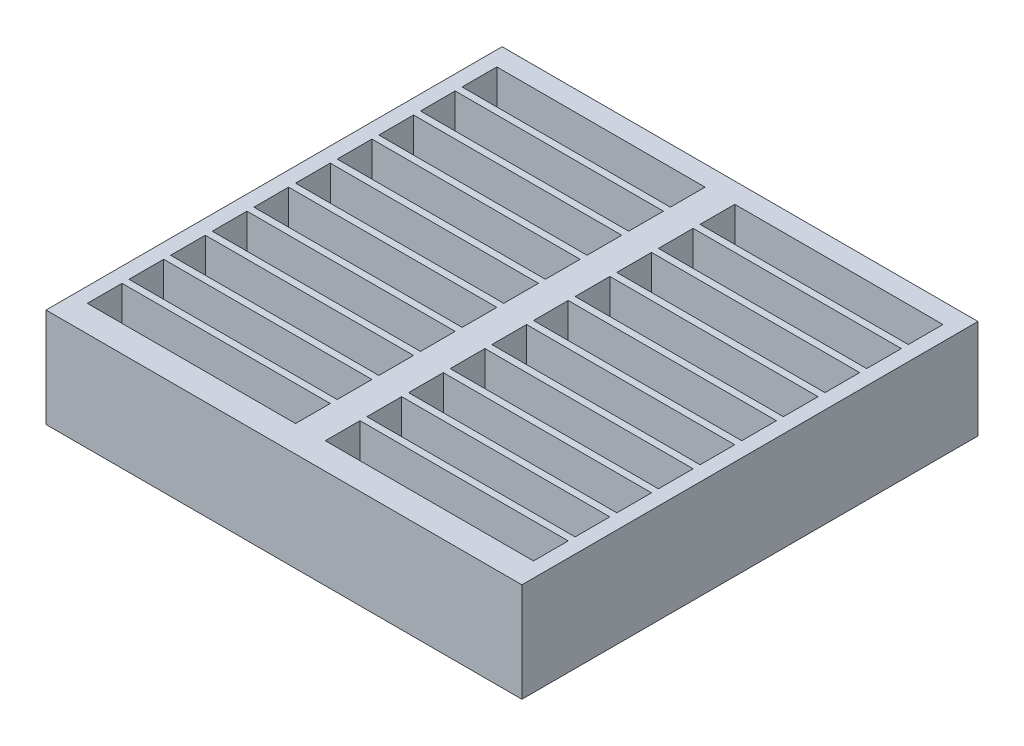
SolidWorks part; units mm, degrees
material "Plastique personnalisé"
ref_plane "Plan de face" through (0, 0, 0) normal (0, 0, 1) x (1, 0, 0)
ref_plane "Plan de dessus" through (0, 0, 0) normal (0, 1, 0) x (1, 0, 0)
ref_plane "Plan de droite" through (0, 0, 0) normal (1, 0, 0) x (0, 0, -1)
sketch "Esquisse1" plane through (0, 0, 0) normal (0, 1, 0) x (1, 0, 0)
  line L1 (0, 0) -> (48, 0)
  line L2 (0, 0) -> (0, 46)
  line L3 (0, 46) -> (48, 46)
  line L4 (48, 0) -> (48, 46)
  dimension "D1" = 48
  dimension "D2" = 46
extrude "Boss.-Extru.1" add sketch "Esquisse1" along normal blind 10
sketch "Esquisse2" plane through (0, 10, 0) normal (0, 1, 0) x (1, 0, 0)
  line L0 (48, 0) -> (0, 0) construction
  line L1 (0, 0) -> (24, 0) construction
  line L2 (24, 0) -> (24, 46) construction
  line L3 (48, 46) -> (0, 46) construction
  line L4 (48, 23) -> (0, 23) construction
  line L5 (48, 0) -> (48, 46) construction
  line L6 (0, 46) -> (0, 0) construction
  line L7 (48, 0) -> (48, 23) construction
  line L8 (48, 11.5) -> (0, 11.5) construction
  line L9 (48, 46) -> (24, 46) construction
  line L10 (36, 46) -> (36, 0) construction
sketch "Esquisse3" plane through (0, 10, 0) normal (0, 1, 0) x (1, 0, 0)
  line L0 (25.5, 2.6693) -> (46.5, 2.6693)
  line L1 (36, 46) -> (36, 0) construction
  line L2 (46.5, 2.6693) -> (46.5, 6.1693)
  line L3 (46.5, 6.1693) -> (25.5, 6.1693)
  line L4 (36, 2.6693) -> (36, 6.1693) construction
  line L5 (25.5, 2.6693) -> (25.5, 6.1693)
  line L6 (25.5, 6.8693) -> (46.5, 6.8693)
  line L7 (46.5, 6.8693) -> (46.5, 10.3693)
  line L8 (46.5, 10.3693) -> (25.5, 10.3693)
  line L9 (25.5, 6.8693) -> (25.5, 10.3693)
  line L10 (25.5, 11.0693) -> (46.5, 11.0693)
  line L11 (46.5, 11.0693) -> (46.5, 14.5693)
  line L12 (46.5, 14.5693) -> (25.5, 14.5693)
  line L13 (25.5, 11.0693) -> (25.5, 14.5693)
  line L14 (25.5, 15.2693) -> (46.5, 15.2693)
  line L15 (46.5, 15.2693) -> (46.5, 18.7693)
  line L16 (46.5, 18.7693) -> (25.5, 18.7693)
  line L17 (25.5, 15.2693) -> (25.5, 18.7693)
  line L18 (25.5, 19.4693) -> (46.5, 19.4693)
  line L19 (46.5, 19.4693) -> (46.5, 22.9693)
  line L20 (46.5, 22.9693) -> (25.5, 22.9693)
  line L21 (25.5, 19.4693) -> (25.5, 22.9693)
  line L22 (25.5, 23.6693) -> (46.5, 23.6693)
  line L23 (46.5, 23.6693) -> (46.5, 27.1693)
  line L24 (46.5, 27.1693) -> (25.5, 27.1693)
  line L25 (25.5, 23.6693) -> (25.5, 27.1693)
  line L26 (25.5, 27.8693) -> (46.5, 27.8693)
  line L27 (46.5, 27.8693) -> (46.5, 31.3693)
  line L28 (46.5, 31.3693) -> (25.5, 31.3693)
  line L29 (25.5, 27.8693) -> (25.5, 31.3693)
  line L30 (25.5, 32.0693) -> (46.5, 32.0693)
  line L31 (46.5, 32.0693) -> (46.5, 35.5693)
  line L32 (46.5, 35.5693) -> (25.5, 35.5693)
  line L33 (25.5, 32.0693) -> (25.5, 35.5693)
  line L34 (25.5, 36.2693) -> (46.5, 36.2693)
  line L35 (46.5, 36.2693) -> (46.5, 39.7693)
  line L36 (46.5, 39.7693) -> (25.5, 39.7693)
  line L37 (25.5, 36.2693) -> (25.5, 39.7693)
  line L38 (25.5, 40.4693) -> (46.5, 40.4693)
  line L39 (46.5, 40.4693) -> (46.5, 43.9693)
  line L40 (46.5, 43.9693) -> (25.5, 43.9693)
  line L41 (25.5, 40.4693) -> (25.5, 43.9693)
  line L43 (24, 0) -> (24, 46) construction
  line L44 (48, 0) -> (0, 0) construction
  line L45 (22.5, 2.6693) -> (22.5, 6.1693)
  line L46 (1.5, 6.1693) -> (22.5, 6.1693)
  line L47 (1.5, 2.6693) -> (1.5, 6.1693)
  line L48 (22.5, 2.6693) -> (1.5, 2.6693)
  line L49 (22.5, 6.8693) -> (22.5, 10.3693)
  line L50 (1.5, 10.3693) -> (22.5, 10.3693)
  line L51 (1.5, 6.8693) -> (1.5, 10.3693)
  line L52 (22.5, 6.8693) -> (1.5, 6.8693)
  line L53 (22.5, 11.0693) -> (22.5, 14.5693)
  line L54 (1.5, 14.5693) -> (22.5, 14.5693)
  line L55 (1.5, 11.0693) -> (1.5, 14.5693)
  line L56 (22.5, 11.0693) -> (1.5, 11.0693)
  line L57 (22.5, 15.2693) -> (22.5, 18.7693)
  line L58 (1.5, 18.7693) -> (22.5, 18.7693)
  line L59 (1.5, 15.2693) -> (1.5, 18.7693)
  line L60 (22.5, 15.2693) -> (1.5, 15.2693)
  line L61 (22.5, 19.4693) -> (22.5, 22.9693)
  line L62 (1.5, 22.9693) -> (22.5, 22.9693)
  line L63 (1.5, 19.4693) -> (1.5, 22.9693)
  line L64 (22.5, 19.4693) -> (1.5, 19.4693)
  line L65 (22.5, 23.6693) -> (22.5, 27.1693)
  line L66 (1.5, 27.1693) -> (22.5, 27.1693)
  line L67 (1.5, 23.6693) -> (1.5, 27.1693)
  line L68 (22.5, 23.6693) -> (1.5, 23.6693)
  line L69 (22.5, 27.8693) -> (22.5, 31.3693)
  line L70 (1.5, 31.3693) -> (22.5, 31.3693)
  line L71 (1.5, 27.8693) -> (1.5, 31.3693)
  line L72 (22.5, 27.8693) -> (1.5, 27.8693)
  line L73 (22.5, 32.0693) -> (22.5, 35.5693)
  line L74 (1.5, 35.5693) -> (22.5, 35.5693)
  line L75 (1.5, 32.0693) -> (1.5, 35.5693)
  line L76 (22.5, 32.0693) -> (1.5, 32.0693)
  line L77 (22.5, 36.2693) -> (22.5, 39.7693)
  line L78 (1.5, 39.7693) -> (22.5, 39.7693)
  line L79 (1.5, 36.2693) -> (1.5, 39.7693)
  line L80 (22.5, 36.2693) -> (1.5, 36.2693)
  line L81 (22.5, 40.4693) -> (22.5, 43.9693)
  line L82 (1.5, 43.9693) -> (22.5, 43.9693)
  line L83 (1.5, 40.4693) -> (1.5, 43.9693)
  line L84 (22.5, 40.4693) -> (1.5, 40.4693)
  dimension "D1" = 10.5
  dimension "D2" = 3.5
  dimension "D3" = 10
  dimension "D4" = 10
extrude "Enlèv. mat.-Extru.1" cut sketch "Esquisse3" against normal blind 10
